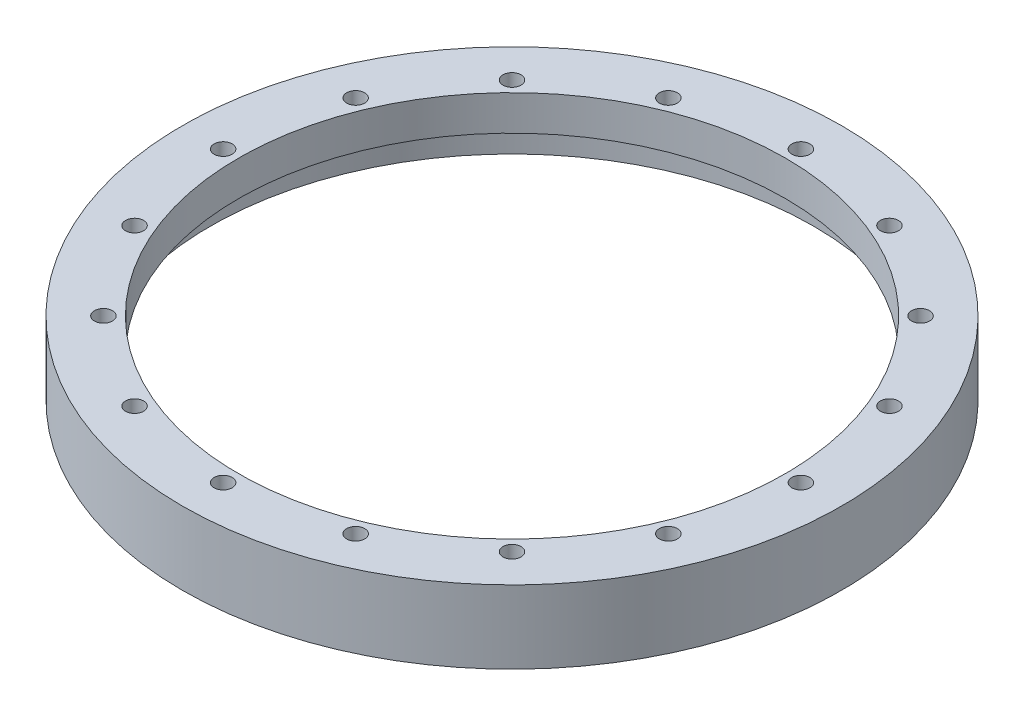
SolidWorks part; units mm, degrees
material "6061-T6 (SS)"
ref_plane "Front Plane" through (0, 0, 0) normal (0, 0, 1) x (1, 0, 0)
ref_plane "Top Plane" through (0, 0, 0) normal (0, 1, 0) x (1, 0, 0)
ref_plane "Right Plane" through (0, 0, 0) normal (1, 0, 0) x (0, 0, -1)
sketch "Sketch1" plane through (0, 0, 0) normal (0, 0, 1) x (1, 0, 0)
  line L0 (-49.4665, 0) -> (-59.6265, 0)
  line L1 (-59.6265, 0) -> (-59.6265, -13.208)
  line L2 (-59.6265, -13.208) -> (-54.5465, -13.208)
  line L3 (-54.5465, -13.208) -> (-54.5465, -6.35)
  line L4 (-54.5465, -6.35) -> (-49.4665, -6.35)
  line L5 (-49.4665, -6.35) -> (-49.4665, 0)
  line L6 (0, 0) -> (0, 8.0765) construction
  dimension "D1" = 49.4665
  dimension "D2" = 54.5465
  dimension "D3" = 5.08
  dimension "D4" = 13.208
  dimension "D5" = 6.35
revolve "Revolve1" add sketch "Sketch1" angle 360 about L6
sketch "Sketch2" plane through (0, 0, 0) normal (0, 1, 0) x (1, 0, 0)
  line L0 (0, 49.4665) -> (0, 52.2681) construction
  circle A0 centre (0, 0) radius 49.4665 construction
  dimension "D1" = 52.2681
hole_wizard "#4 Clearance Hole1" positions "3DSketch1" profile "Sketch3" hole size "#4" standard "Ansi Inch"
sketch3d "3DSketch1"
  point P0 (0, 0, -52.2681)
sketch "Sketch3" plane through (0, 0, -52.2681) normal (1, 0, 0) x (0, 0, 1)
  line L0 (0, 0) -> (0, 11.1406)
  line L1 (0, 11.1406) -> (1.6319, 10.16)
  line L2 (1.6319, 10.16) -> (1.6319, 0)
  line L5 (1.6319, 0) -> (0, 0)
  line L10 (0, 11.1406) -> (-1.632, 10.16) construction
  line L11 (0, -6.35) -> (0, 107.95) construction
  dimension "Hole Dia." = 3.2639
  dimension "Hole Depth" = 10.16
  dimension "Drill Angle" = 118
pattern_circular "CirPattern1" count 16 over 360 about axis through (0, 0, 0) along (0, 1, 0) of "#4 Clearance Hole1"
